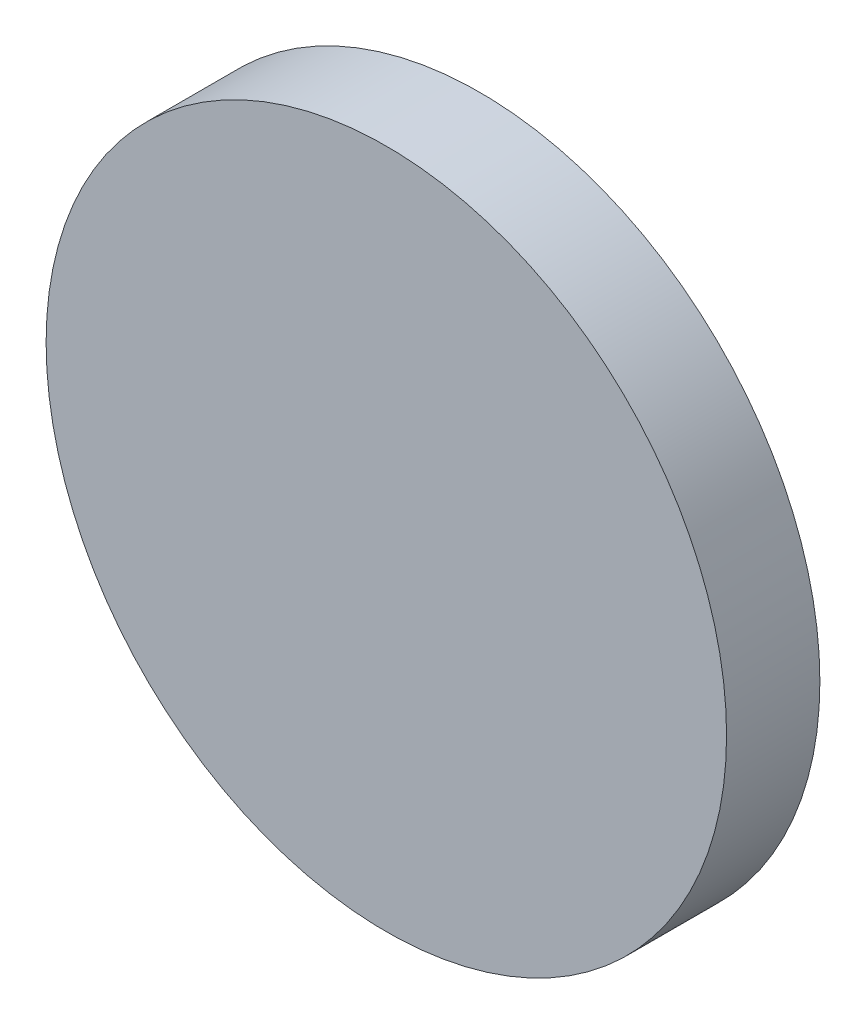
SolidWorks part; units mm, degrees
ref_plane "Спереди" through (0, 0, 0) normal (0, 0, 1) x (1, 0, 0)
ref_plane "Сверху" through (0, 0, 0) normal (0, 1, 0) x (1, 0, 0)
ref_plane "Справа" through (0, 0, 0) normal (1, 0, 0) x (0, 0, -1)
sketch "Эскиз1" plane through (0, 0, 0) normal (0, 0, 1) x (1, 0, 0)
  circle A0 centre (-69.0181, 21.205) radius 72.9226
extrude "Бобышка-Вытянуть1" add sketch "Эскиз1" along normal blind 20
